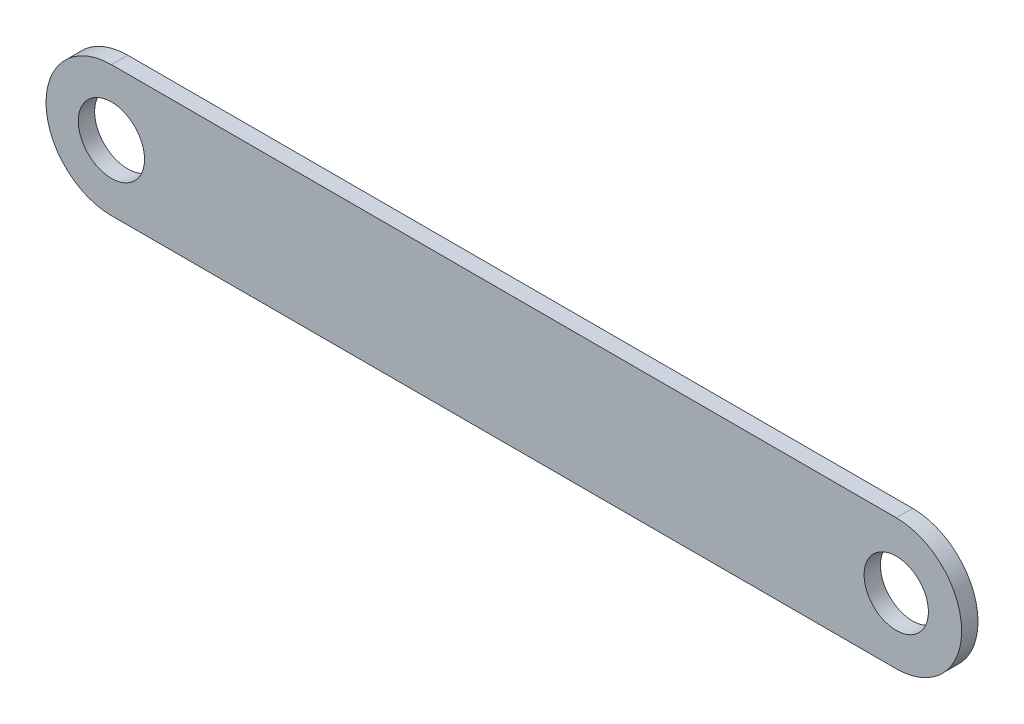
SolidWorks part; units mm, degrees
ref_plane "Front Plane" through (0, 0, 0) normal (0, 0, 1) x (1, 0, 0)
ref_plane "Top Plane" through (0, 0, 0) normal (0, 1, 0) x (1, 0, 0)
ref_plane "Right Plane" through (0, 0, 0) normal (1, 0, 0) x (0, 0, -1)
sketch "Sketch1" plane through (0, 0, 0) normal (0, 0, 1) x (1, 0, 0)
  line L0 (0, 0) -> (152.4, 0) construction
  line L1 (0, 12.7) -> (152.4, 12.7)
  line L2 (0, -12.7) -> (152.4, -12.7)
  arc A0 (0, 12.7) -> (0, -12.7) centre (0, 0) ccw
  arc A1 (152.4, -12.7) -> (152.4, 12.7) centre (152.4, 0) ccw
  circle A2 centre (0, 0) radius 6.4301
  circle A3 centre (152.4, 0) radius 6.2478
  point P3 (76.2, 0)
  dimension "D1" = 25.4
  dimension "D2" = 152.4
extrude "Boss-Extrude1" add sketch "Sketch1" along normal blind 3.175
